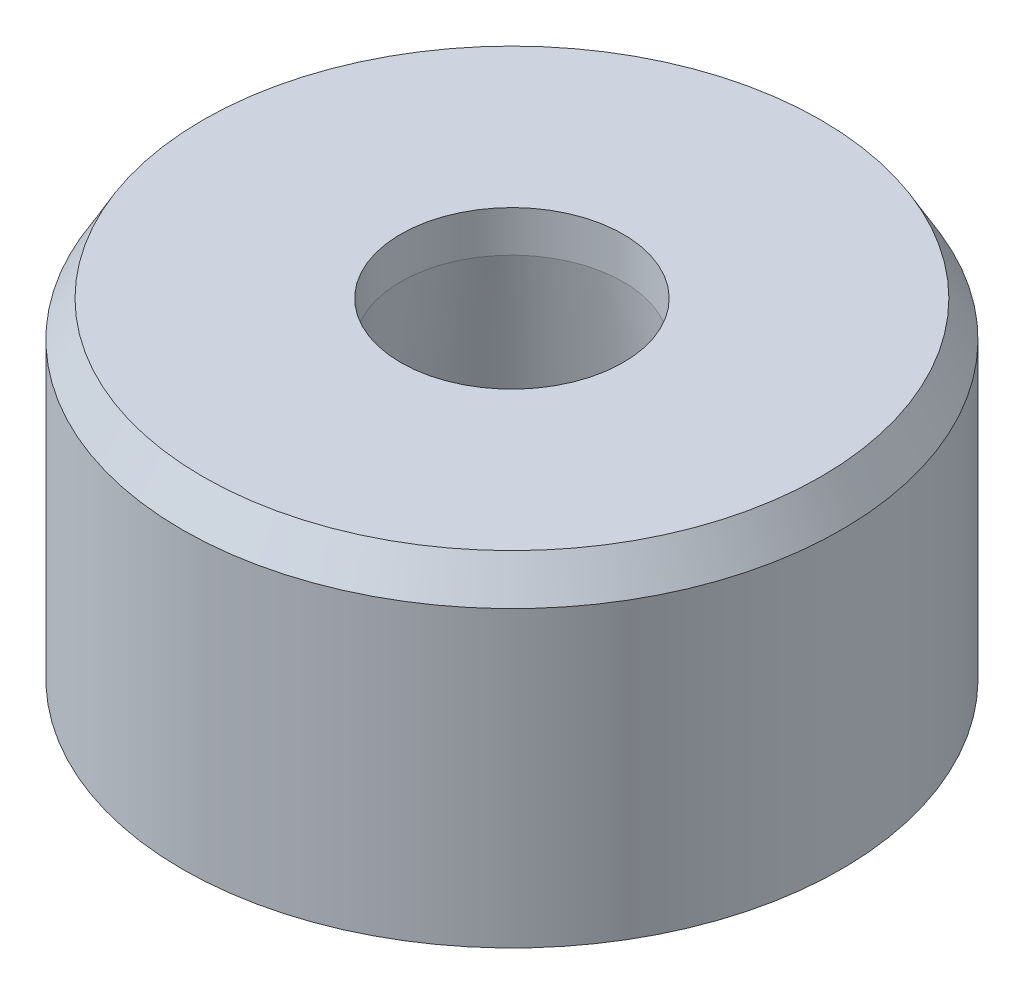
SolidWorks part; units mm, degrees
ref_plane "Front" through (0, 0, 0) normal (0, 0, 1) x (1, 0, 0)
ref_plane "Top" through (0, 0, 0) normal (0, 1, 0) x (1, 0, 0)
ref_plane "Right" through (0, 0, 0) normal (1, 0, 0) x (0, 0, -1)
sketch "Sketch1" plane through (0, 0, 0) normal (0, 1, 0) x (1, 0, 0)
  circle A0 centre (0, 0) radius 2.7
  circle A1 centre (0, 0) radius 8
  dimension "D1" = 5.4
  dimension "D2" = 16
extrude "Boss-Extrude1" add sketch "Sketch1" along normal blind 8
chamfer "Chamfer1" distance 7 angle 8 1 edges at (0, 0, 2.7)
chamfer "Chamfer2" distance 0.5 angle 60 1 edges at (0, 8, 8)
equation "\"height\"= 13 - 5"
equation "\"D1@Boss-Extrude1\"=\"height\""
